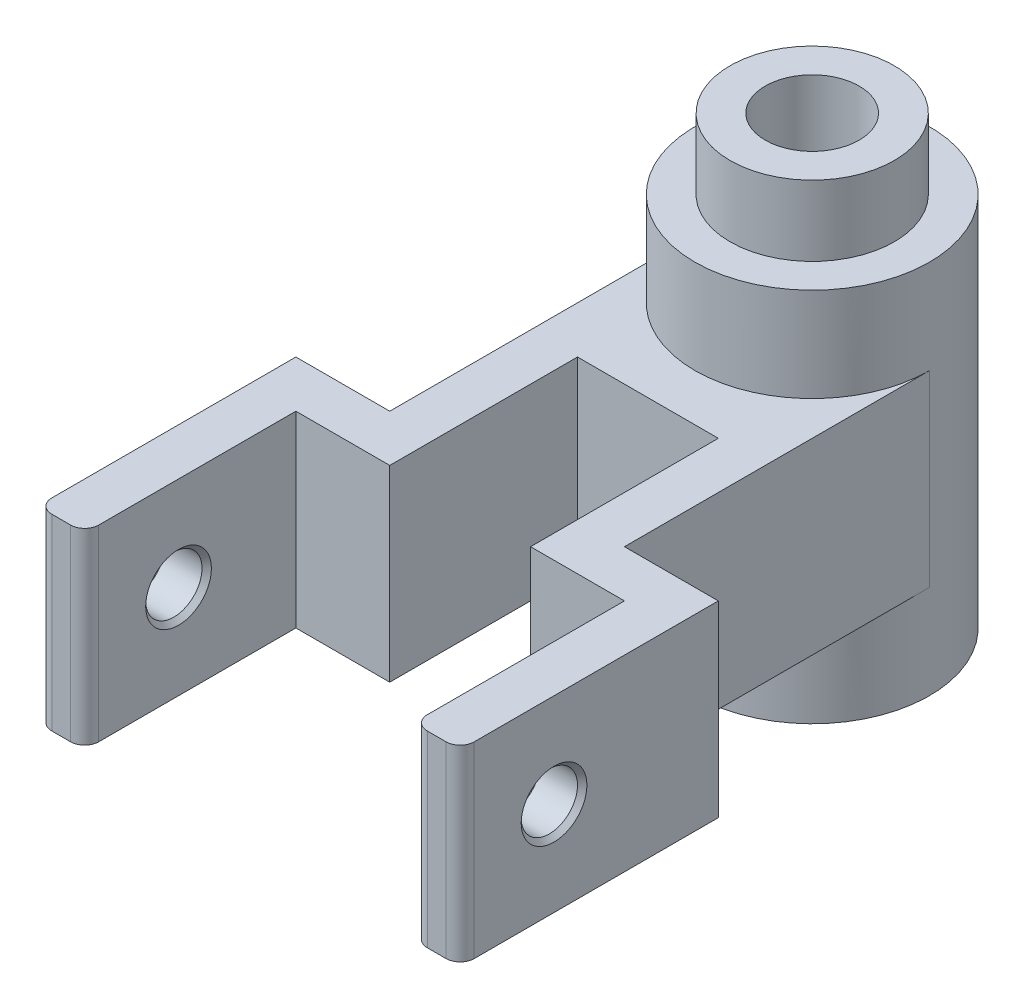
SolidWorks part; units mm, degrees
ref_plane "Front Plane" through (0, 0, 0) normal (0, 0, 1) x (1, 0, 0)
ref_plane "Top Plane" through (0, 0, 0) normal (0, 1, 0) x (1, 0, 0)
ref_plane "Right Plane" through (0, 0, 0) normal (1, 0, 0) x (0, 0, -1)
sketch "Sketch1" plane through (0, 0, 0) normal (0, 1, 0) x (1, 0, 0)
  line L0 (0, 0) -> (0, 45)
  line L1 (0, 45) -> (20, 45)
  line L2 (20, 45) -> (20, 85)
  line L3 (20, 85) -> (50, 85)
  line L4 (50, 85) -> (50, 45)
  line L5 (50, 45) -> (70, 45)
  line L6 (70, 45) -> (70, 0)
  line L7 (70, 0) -> (80, 0)
  line L8 (80, 0) -> (80, 55)
  line L9 (80, 55) -> (60, 55)
  line L10 (60, 55) -> (60, 120)
  line L11 (60, 120) -> (10, 120)
  line L12 (10, 120) -> (10, 55)
  line L13 (10, 55) -> (-10, 55)
  line L14 (-10, 55) -> (-10, 0)
  line L15 (-10, 0) -> (0, 0)
  dimension "D1" = 45
  dimension "D2" = 55
  dimension "D3" = 10
  dimension "D4" = 55
  dimension "D5" = 45
  dimension "D6" = 10
  dimension "D7" = 65
  dimension "D8" = 65
  dimension "D9" = 40
  dimension "D10" = 35
  dimension "D11" = 20
  dimension "D12" = 20
  dimension "D13" = 20
  dimension "D14" = 20
  dimension "D15" = 40
  dimension "D16" = 30
extrude "Boss-Extrude2" add sketch "Sketch1" along normal mid plane 40
fillet "Fillet10" radius 3 4 edges at (80, 0, 0) (70, 0, 0) (-10, 0, 0) (0, 0, 0)
sketch "Sketch2" plane through (80, 0, 0) normal (1, 0, 0) x (0, 0, -1)
  line L0 (55, -20) -> (3, -20) construction
  line L1 (20, 20) -> (20, -20) construction
  line L3 (3, 20) -> (55, 20) construction
  line L4 (3, 20) -> (0, 20) construction
  line L6 (3, -20) -> (55, -20) construction
  circle A0 centre (20, 0) radius 6
  point P2 (29, -20)
  point P9 (1.5, 20)
  point P10 (29, 20)
  point P11 (1.5, 20)
  point P15 (1.5, 20)
  point P16 (20, 0)
  dimension "D1" = 20
  dimension "D2" = 12
extrude "Cut-Extrude1" cut sketch "Sketch2" against normal through all
sketch "Sketch3" plane through (0, 0, 0) normal (0, 1, 0) x (1, 0, 0)
  line L0 (20, 85) -> (50, 85) construction
  line L2 (35, 145.7798) -> (35, 90.6654) construction
  line L3 (68.946, 120) -> (-2.3856, 120) construction
  circle A0 centre (35, 120) radius 25
  circle A1 centre (35, 120) radius 17.5 construction
  point P2 (35, 85)
  dimension "D1" = 50
  dimension "D2" = 35
extrude "Boss-Extrude6" add sketch "Sketch3" along normal mid plane 80
sketch "Sketch5" plane through (0, 40, 0) normal (0, 1, 0) x (1, 0, 0)
  circle A0 centre (35, 120) radius 17.5
  dimension "D1" = 35
extrude "Boss-Extrude7" add sketch "Sketch5" along normal mid plane 30
sketch "Sketch6" plane through (0, 55, 0) normal (0, 1, 0) x (1, 0, 0)
  circle A0 centre (35, 120) radius 10
  dimension "D1" = 20
extrude "Cut-Extrude2" cut sketch "Sketch6" against normal through all
chamfer "Chamfer1" distance 1 angle 45 4 edges at (70, 0, -26) (-10, 0, -26) (0, 0, -14) (80, 0, -26)
